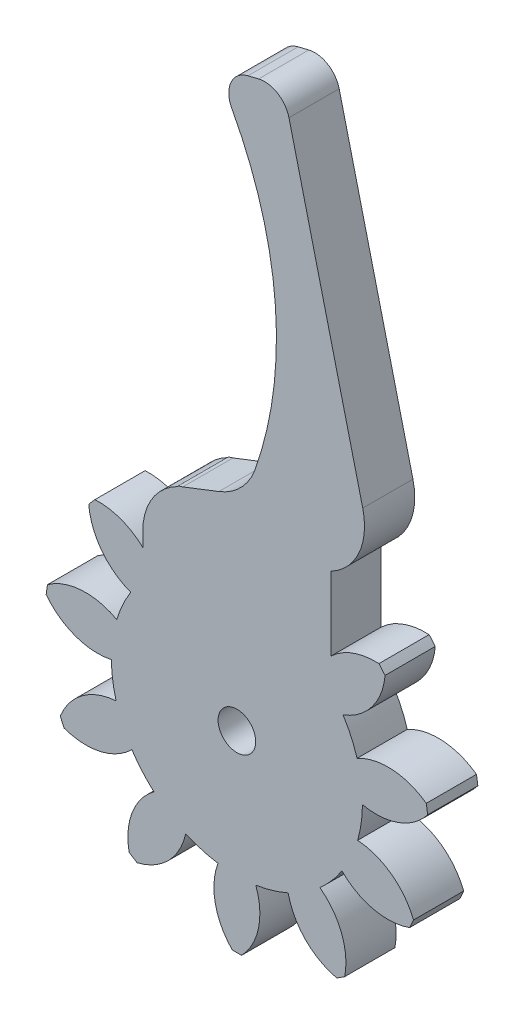
SolidWorks part; units mm, degrees
ref_plane "Спереди" through (0, 0, 0) normal (0, 0, 1) x (1, 0, 0)
ref_plane "Сверху" through (0, 0, 0) normal (0, 1, 0) x (1, 0, 0)
ref_plane "Справа" through (0, 0, 0) normal (1, 0, 0) x (0, 0, -1)
other "Configuration Table"
sketch "Эскиз1" plane through (0, 0, 0) normal (0, 0, 1) x (1, 0, 0)
  arc A1 (14.0713, -6.0135) -> (9.622, -2.739) centre (9.2497, -7.9048) ccw
  arc A2 (9.622, -2.739) -> (10.0039, -0.0828) centre (0, 0) ccw
  arc A3 (10.0039, -0.0828) -> (15.1955, 1.8056) centre (11.1021, 4.9787) ccw
  arc A4 (15.1955, 1.8056) -> (15.0886, 2.5486) centre (0, 0) ccw
  arc A5 (15.0886, 2.5486) -> (9.5753, 2.8979) centre (12.055, -1.6492) ccw
  arc A6 (9.5753, 2.8979) -> (8.4606, 5.3388) centre (0, 0) ccw
  arc A7 (8.4606, 5.3388) -> (11.8071, 9.7342) centre (6.648, 10.1906) ccw
  arc A8 (11.8071, 9.7342) -> (11.3155, 10.3016) centre (0, 0) ccw
  arc A9 (3.9497, 14.7838) -> (1.3417, 9.9138) centre (6.508, 10.2805) ccw
  arc A10 (1.3417, 9.9138) -> (-1.3417, 9.9138) centre (0, 0) ccw
  arc A11 (-1.3417, 9.9138) -> (-3.9497, 14.7838) centre (-6.508, 10.2805) ccw
  arc A12 (-3.9497, 14.7838) -> (-4.67, 14.5723) centre (0, 0) ccw
  arc A13 (-4.67, 14.5723) -> (-4.2311, 9.0654) centre (-0.0832, 12.167) ccw
  arc A14 (-4.2311, 9.0654) -> (-6.4886, 7.6147) centre (0, 0) ccw
  arc A15 (-6.4886, 7.6147) -> (-11.3155, 10.3016) centre (-11.0329, 5.13) ccw
  arc A16 (-11.3155, 10.3016) -> (-11.8071, 9.7342) centre (0, 0) ccw
  arc A17 (-11.8071, 9.7342) -> (-8.4606, 5.3388) centre (-6.648, 10.1906) ccw
  arc A18 (-8.4606, 5.3388) -> (-9.5753, 2.8979) centre (0, 0) ccw
  arc A19 (-9.5753, 2.8979) -> (-15.0886, 2.5486) centre (-12.055, -1.6492) ccw
  arc A20 (-15.0886, 2.5486) -> (-15.1955, 1.8056) centre (0, 0) ccw
  arc A21 (-15.1955, 1.8056) -> (-10.0039, -0.0828) centre (-11.1021, 4.9787) ccw
  arc A22 (-10.0039, -0.0828) -> (-9.622, -2.739) centre (0, 0) ccw
  arc A23 (-6.6137, -7.5062) -> (-8.5864, -12.6664) centre (-3.5077, -11.6507) ccw
  arc A24 (-8.5864, -12.6664) -> (-7.9548, -13.0722) centre (0, 0) ccw
  arc A25 (-7.9548, -13.0722) -> (-4.0804, -9.1342) centre (-9.1407, -8.0306) ccw
  arc A26 (-4.0804, -9.1342) -> (-1.5057, -9.8903) centre (0, 0) ccw
  arc A27 (-1.5057, -9.8903) -> (-0.3753, -15.2978) centre (3.348, -11.6976) ccw
  arc A28 (-0.3753, -15.2978) -> (0.3753, -15.2978) centre (0, 0) ccw
  arc A29 (0.3753, -15.2978) -> (1.5057, -9.8903) centre (-3.348, -11.6976) ccw
  arc A30 (1.5057, -9.8903) -> (4.0804, -9.1342) centre (0, 0) ccw
  arc A31 (4.0804, -9.1342) -> (7.9548, -13.0722) centre (9.1407, -8.0306) ccw
  arc A32 (7.9548, -13.0722) -> (8.5864, -12.6664) centre (0, 0) ccw
  arc A33 (8.5864, -12.6664) -> (6.6137, -7.5062) centre (3.5077, -11.6507) ccw
  arc A34 (6.6137, -7.5062) -> (8.371, -5.4782) centre (0, 0) ccw
  arc A35 (8.371, -5.4782) -> (13.7594, -6.6963) centre (12.0313, -1.8139) ccw
  arc A36 (13.7594, -6.6963) -> (14.0713, -6.0135) centre (0, 0) ccw
  arc A37 (-9.622, -2.739) -> (-14.0713, -6.0135) centre (-9.2497, -7.9048) ccw
  arc A38 (-14.0713, -6.0135) -> (-13.7594, -6.6963) centre (0, 0) ccw
  arc A39 (-13.7594, -6.6963) -> (-8.371, -5.4782) centre (-12.0313, -1.8139) ccw
  arc A40 (-8.371, -5.4782) -> (-6.6137, -7.5062) centre (0, 0) ccw
  arc A41 (11.3155, 10.3016) -> (6.4886, 7.6147) centre (11.0329, 5.13) ccw
  arc A42 (6.4886, 7.6147) -> (4.2311, 9.0654) centre (0, 0) ccw
  arc A43 (4.2311, 9.0654) -> (4.67, 14.5723) centre (0.0832, 12.167) ccw
  arc A44 (4.67, 14.5723) -> (3.9497, 14.7838) centre (0, 0) ccw
  circle A45 centre (0, 0) radius 1.5
  dimension "D3" = 3
extrude "Бобышка-Вытянуть1" add sketch "Эскиз1" along normal blind 4
sketch "Эскиз2" plane through (0, 0, 4) normal (0, 0, 1) x (1, 0, 0)
  line L2 (0, 45.4292) -> (0, 0) construction
  line L4 (-7.5, 10.0221) -> (-7.5, 0)
  line L9 (-4.3112, 14.6825) -> (-1.4383, 15.799)
  line L12 (10.0262, 20.3866) -> (4.1485, 44.3861)
  line L15 (7.5, 14.7734) -> (7.5, 0)
  line L16 (0.8769, 45.644) -> (1.7301, 45.8529)
  arc A14 (-7.5, 0) -> (7.5, 0) centre (0, 0) ccw
  arc A15 (-1.4383, 15.799) -> (1.3839, 18.5801) centre (-3.2495, 20.4594) ccw
  arc A16 (7.5, 14.7734) -> (10.0262, 20.3866) centre (5.1697, 19.1972) ccw
  arc A19 (-7.5, 10.0221) -> (-4.3112, 14.6825) centre (-2.5, 10.0221) cw
  arc A20 (1.3839, 18.5801) -> (-0.4073, 42.7514) centre (-26.5032, 28.6656) ccw
  circle A21 centre (0, 0) radius 1.5
  arc A22 (-3.9497, 14.7838) -> (-4.67, 14.5723) centre (0, 0) ccw construction
  arc A23 (1.7301, 45.8529) -> (4.1485, 44.3861) centre (2.2059, 43.9103) cw
  arc A24 (0.8769, 45.644) -> (-0.4073, 42.7514) centre (1.3527, 43.7014) ccw
  point P0 (0, 30)
  point P17 (-1.7526, 45)
  point P24 (2.774, 19.346)
  dimension "D1" = 2
  dimension "D2" = 45
extrude "Бобышка-Вытянуть2" add sketch "Эскиз2" against normal blind 4
